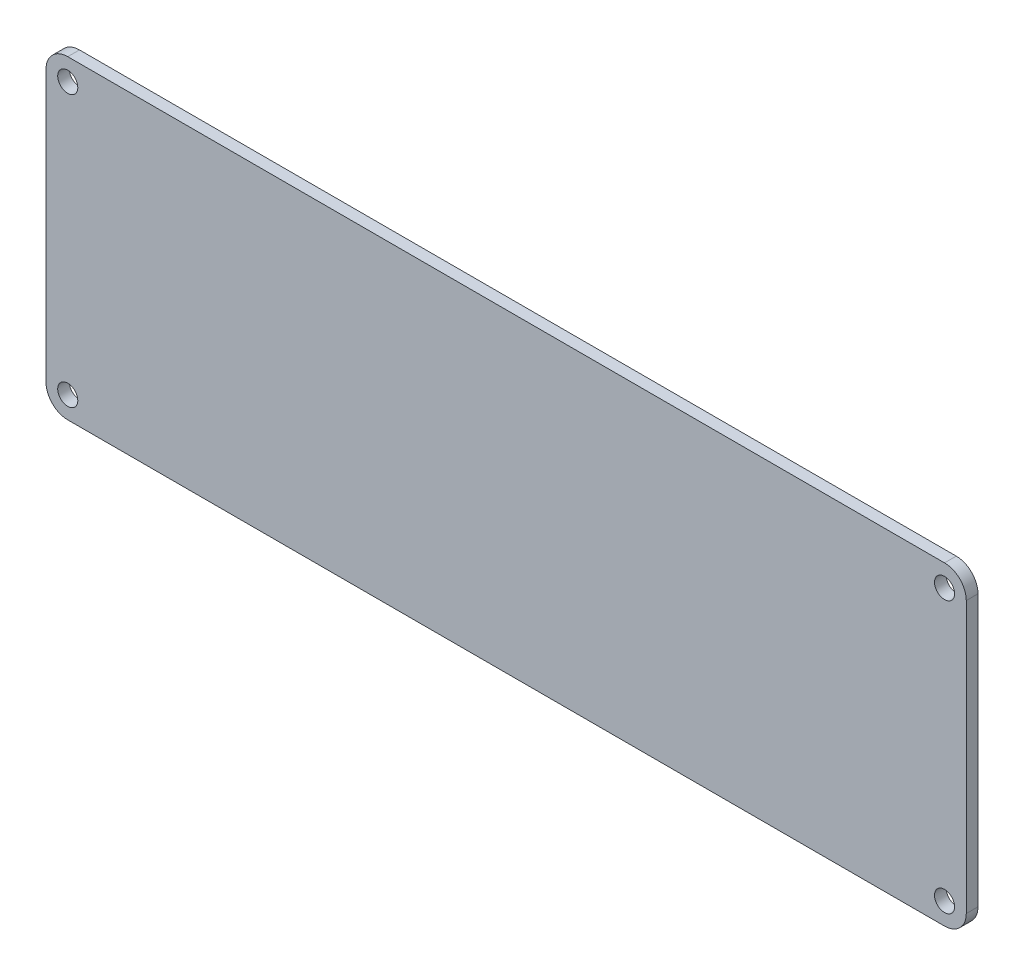
SolidWorks part; units mm, degrees
material "处理板，简单型"
ref_plane "前视基准面" through (0, 0, 0) normal (0, 0, 1) x (1, 0, 0)
ref_plane "上视基准面" through (0, 0, 0) normal (0, 1, 0) x (1, 0, 0)
ref_plane "右视基准面" through (0, 0, 0) normal (1, 0, 0) x (0, 0, -1)
sketch "草图1" plane through (0, 0, 0) normal (0, 0, 1) x (1, 0, 0)
  line L1 (3.302, 0) -> (136.398, 0)
  line L2 (0, 3.302) -> (0, 44.45)
  line L3 (3.302, 47.752) -> (136.398, 47.752)
  line L4 (139.7, 3.302) -> (139.7, 44.45)
  arc A0 (3.302, 47.752) -> (0, 44.45) centre (3.302, 44.45) ccw
  arc A1 (139.7, 44.45) -> (136.398, 47.752) centre (136.398, 44.45) ccw
  arc A2 (136.398, 0) -> (139.7, 3.302) centre (136.398, 3.302) ccw
  arc A3 (3.302, 0) -> (0, 3.302) centre (3.302, 3.302) cw
  circle A4 centre (3.302, 44.45) radius 1.524
  circle A5 centre (136.398, 44.45) radius 1.524
  circle A6 centre (136.398, 3.302) radius 1.524
  circle A7 centre (3.302, 3.302) radius 1.524
  point P13 (0, 0)
  dimension "D1" = 3.302
  dimension "D2" = 3.302
  dimension "D3" = 3.302
  dimension "D4" = 3.302
extrude "凸台-拉伸1" add sketch "草图1" along normal blind 1.778
